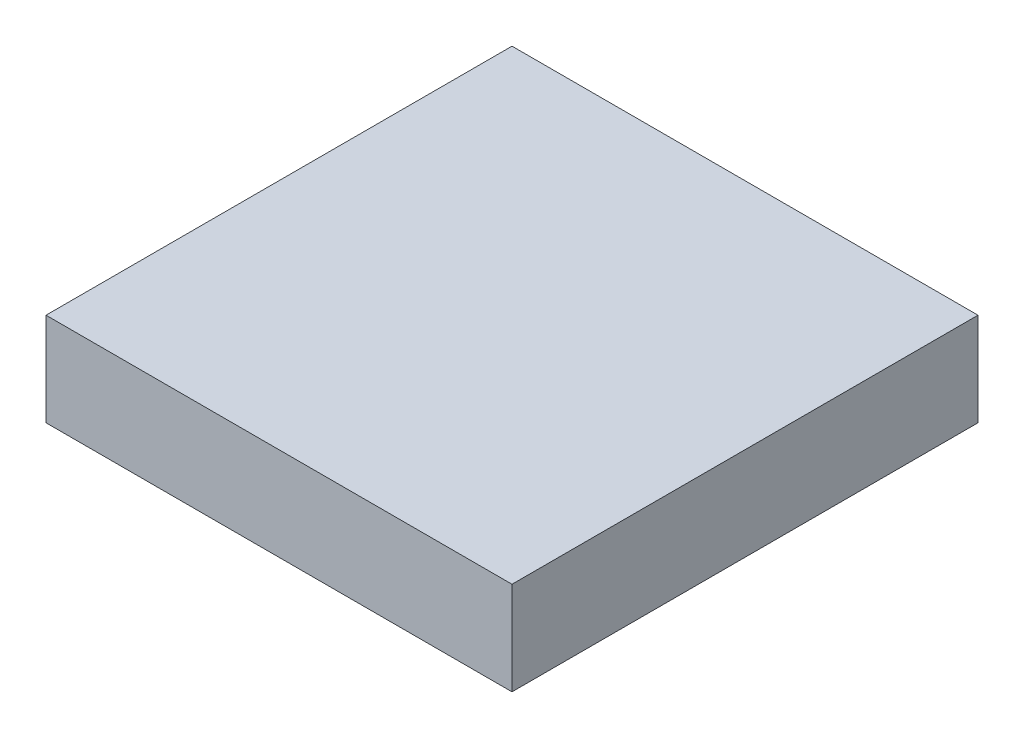
SolidWorks part; units mm, degrees
material "1.0725 (15SMn13)"
ref_plane "Přední rovina" through (0, 0, 0) normal (0, 0, 1) x (1, 0, 0)
ref_plane "Horní rovina" through (0, 0, 0) normal (0, 1, 0) x (1, 0, 0)
ref_plane "Pravá rovina" through (0, 0, 0) normal (1, 0, 0) x (0, 0, -1)
sketch "Skica1" plane through (0, 0, 0) normal (0, 1, 0) x (1, 0, 0)
  line L1 (5, -5) -> (-5, -5)
  line L2 (5, -5) -> (5, 5)
  line L3 (5, 5) -> (-5, 5)
  line L4 (-5, -5) -> (-5, 5)
  line L5 (5, -5) -> (-5, 5) construction
  line L6 (5, 5) -> (-5, -5) construction
  point P0 (0, 0)
  dimension "D1" = 10
extrude "Přidat vysunutím1" add sketch "Skica1" along normal blind 2
